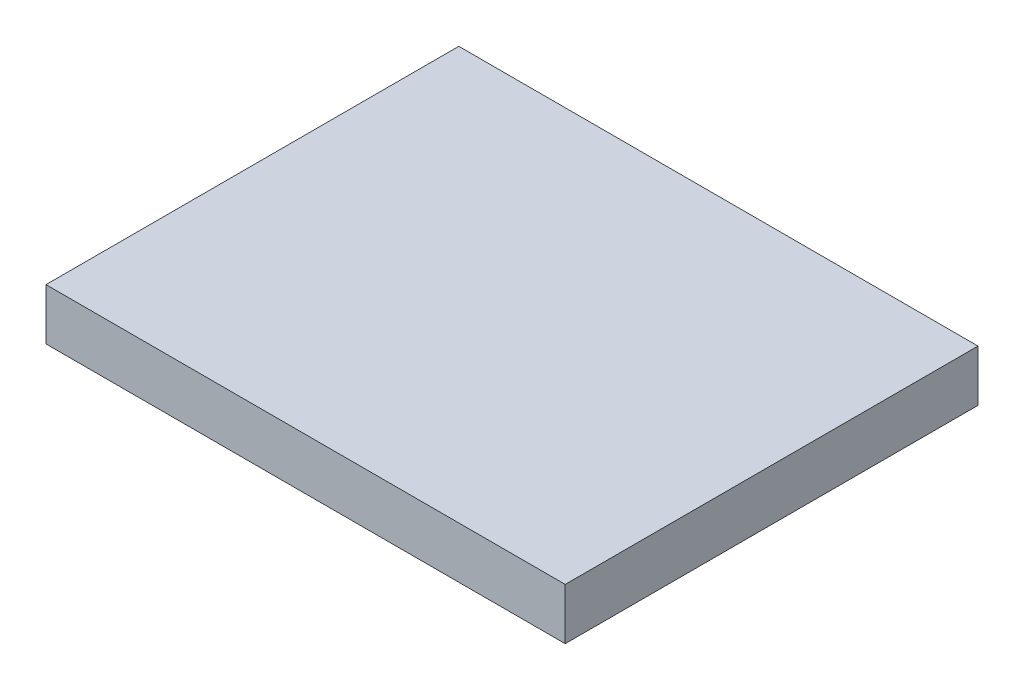
SolidWorks part; units mm, degrees
ref_plane "Front Plane" through (0, 0, 0) normal (0, 0, 1) x (1, 0, 0)
ref_plane "Top Plane" through (0, 0, 0) normal (0, 1, 0) x (1, 0, 0)
ref_plane "Right Plane" through (0, 0, 0) normal (1, 0, 0) x (0, 0, -1)
sketch "Sketch1" plane through (0, 0, 0) normal (0, 1, 0) x (1, 0, 0)
  line L1 (0, 0) -> (283, 0)
  line L2 (0, 0) -> (0, 225)
  line L3 (0, 225) -> (283, 225)
  line L4 (283, 0) -> (283, 225)
  dimension "D1" = 225
  dimension "D2" = 283
extrude "Boss-Extrude1" add sketch "Sketch1" along normal blind 28
